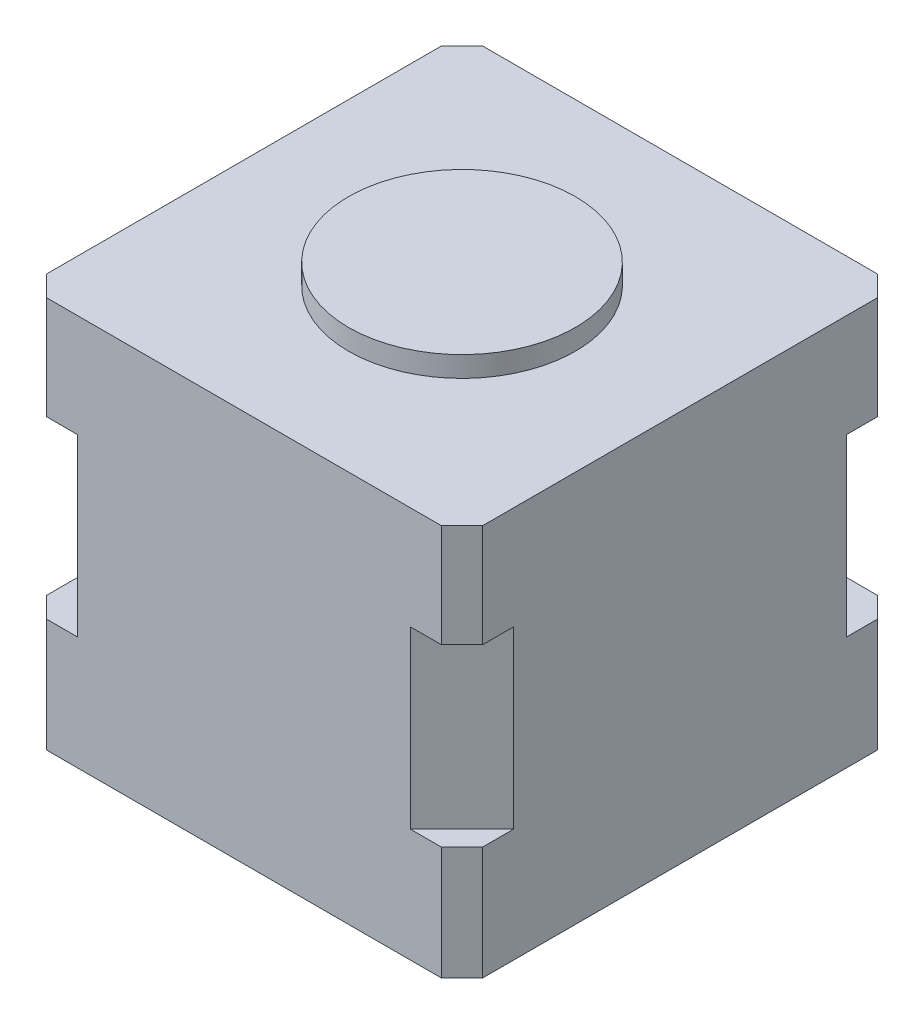
SolidWorks part; units mm, degrees
ref_plane "Front Plane" through (0, 0, 0) normal (0, 0, 1) x (1, 0, 0)
ref_plane "Top Plane" through (0, 0, 0) normal (0, 1, 0) x (1, 0, 0)
ref_plane "Right Plane" through (0, 0, 0) normal (1, 0, 0) x (0, 0, -1)
sketch "Sketch1" plane through (0, 0, 0) normal (0, 1, 0) x (1, 0, 0)
  line L0 (19.15, -21.15) -> (21.15, -19.15)
  line L1 (-19.15, 21.15) -> (19.15, 21.15)
  line L2 (-21.15, 19.15) -> (-21.15, -19.15)
  line L3 (-19.15, -21.15) -> (19.15, -21.15)
  line L4 (21.15, 19.15) -> (21.15, -19.15)
  line L5 (-21.15, 21.15) -> (21.15, -21.15) construction
  line L6 (-21.15, -21.15) -> (21.15, 21.15) construction
  line L7 (-21.15, -19.15) -> (-19.15, -21.15)
  line L8 (-21.15, 19.15) -> (-19.15, 21.15)
  line L9 (19.15, 21.15) -> (21.15, 19.15)
  point P0 (0, 0)
  dimension "D1" = 42.3
  dimension "D2" = 42.3
  dimension "D3" = 2
  dimension "D4" = 45
  dimension "D5" = 2
  dimension "D6" = 45
  dimension "D7" = 2
  dimension "D8" = 45
  dimension "D9" = 2
  dimension "D10" = 45
extrude "Boss-Extrude1" add sketch "Sketch1" along normal blind 11
sketch "Sketch2" plane through (0, 11, 0) normal (0, 1, 0) x (1, 0, 0)
  line L0 (16.15, -21.15) -> (21.15, -16.15)
  line L1 (-16.15, 21.15) -> (16.15, 21.15)
  line L2 (-21.15, 16.15) -> (-21.15, -16.15)
  line L3 (-16.15, -21.15) -> (16.15, -21.15)
  line L4 (21.15, 16.15) -> (21.15, -16.15)
  line L5 (-21.15, 21.15) -> (21.15, -21.15) construction
  line L6 (-21.15, -21.15) -> (21.15, 21.15) construction
  line L7 (-21.15, -16.15) -> (-16.15, -21.15)
  line L8 (16.15, 21.15) -> (21.15, 16.15)
  line L9 (-21.15, 16.15) -> (-16.15, 21.15)
  point P0 (0, 0)
  dimension "D1" = 42.3
  dimension "D2" = 42.3
extrude "Boss-Extrude2" add sketch "Sketch2" along normal blind 17
sketch "Sketch3" plane through (0, 28, 0) normal (0, 1, 0) x (1, 0, 0)
  line L0 (19.15, -21.15) -> (21.15, -19.15)
  line L1 (-19.15, 21.15) -> (19.15, 21.15)
  line L2 (-21.15, 19.15) -> (-21.15, -19.15)
  line L3 (-19.15, -21.15) -> (19.15, -21.15)
  line L4 (21.15, 19.15) -> (21.15, -19.15)
  line L5 (-21.15, 21.15) -> (21.15, -21.15) construction
  line L6 (-21.15, -21.15) -> (21.15, 21.15) construction
  line L7 (19.15, 21.15) -> (21.15, 19.15)
  line L8 (-21.15, 19.15) -> (-19.15, 21.15)
  line L9 (-21.15, -19.15) -> (-19.15, -21.15)
  point P0 (0, 0)
  dimension "D1" = 42.3
  dimension "D2" = 42.3
extrude "Boss-Extrude3" add sketch "Sketch3" along normal blind 10
sketch "Sketch4" plane through (0, 38, 0) normal (0, 1, 0) x (1, 0, 0)
  circle A0 centre (0, 0) radius 11
  dimension "D1" = 22
extrude "Boss-Extrude4" add sketch "Sketch4" along normal blind 2
